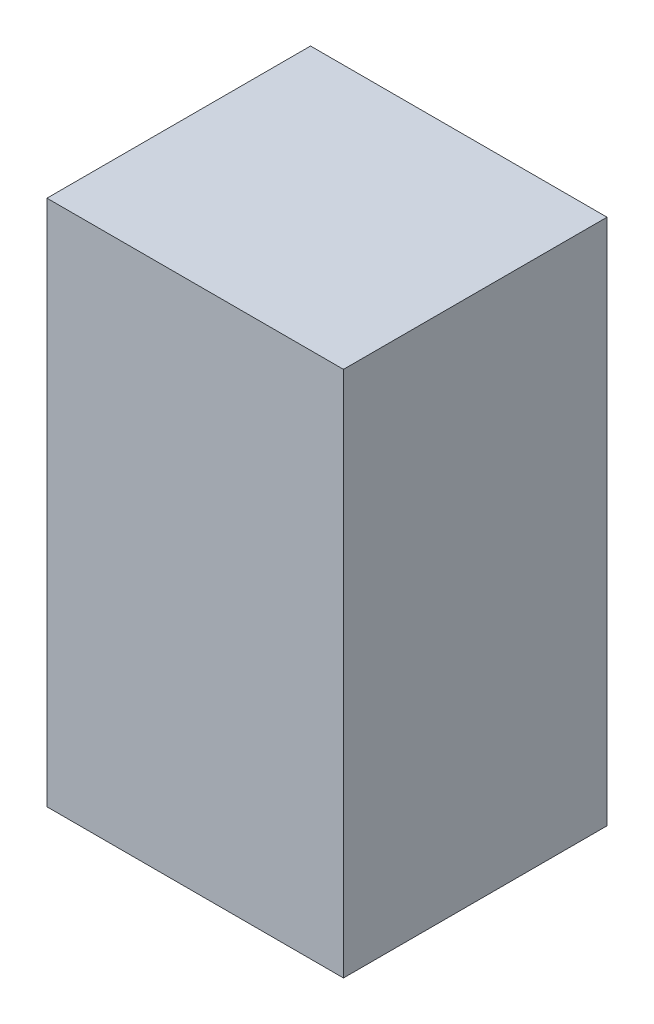
SolidWorks part; units mm, degrees
ref_plane "Front Plane" through (0, 0, 0) normal (0, 0, 1) x (1, 0, 0)
ref_plane "Top Plane" through (0, 0, 0) normal (0, 1, 0) x (1, 0, 0)
ref_plane "Right Plane" through (0, 0, 0) normal (1, 0, 0) x (0, 0, -1)
other "Configuration Table"
sketch "Sketch1" plane through (0, 0, 0) normal (0, 0, 1) x (1, 0, 0)
  line L1 (580, 220) -> (625, 220)
  line L2 (580, 220) -> (580, 300)
  line L3 (580, 300) -> (625, 300)
  line L4 (625, 220) -> (625, 300)
extrude "OVEN_pano_SSR_2_1" add sketch "Sketch1" against normal blind 40 from offset 208 separate body
